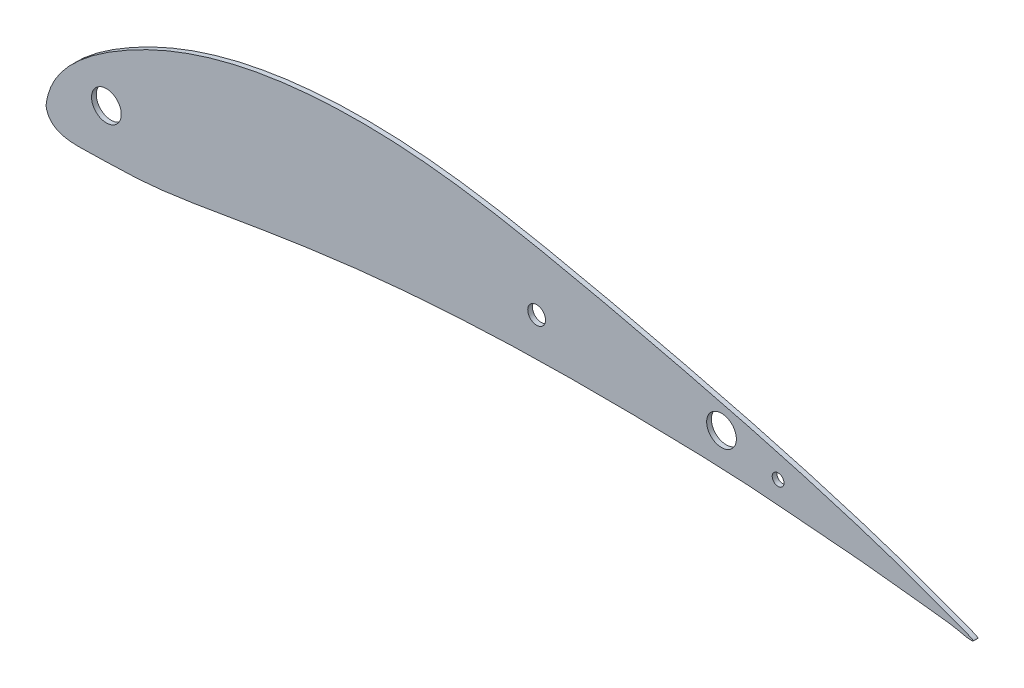
SolidWorks part; units mm, degrees
material "Balsa"
ref_plane "Front Plane" through (0, 0, 0) normal (0, 0, 1) x (1, 0, 0)
ref_plane "Top Plane" through (0, 0, 0) normal (0, 1, 0) x (1, 0, 0)
ref_plane "Right Plane" through (0, 0, 0) normal (1, 0, 0) x (0, 0, -1)
sketch "Sketch1" plane through (0, 0, 0) normal (0, 0, 1) x (1, 0, 0)
  spline S0 degree 3 poles (0.0006, 0.0001) (0.8106, 7.3592) (8.6491, 17.8566) (26.2867, 29.9752) (52.1111, 42.0692) (89.5976, 49.2908) (131.4008, 47.8848) (173.2567, 40.0411) (217.9611, 29.613) (256.9521, 19.5289) (290.3598, 8.711) (301.2732, 4.3828) (314.8169, -0.5162) (309.8463, 0.0001) knots 0 0 0 0 0.060864 0.113688 0.188609 0.312909 0.448482 0.557612 0.691544 0.852438 0.929756 0.976058 1 1 1 1
  spline S1 degree 3 poles (309.8463, 0.0001) (303.9568, 1.471) (293.9895, 2.094) (276.264, 4.5144) (260.8463, 5.4274) (235.8588, 7.8703) (205.1014, 8.8381) (157.7186, 9.0307) (110.4973, 6.1815) (66.5062, -0.5867) (36.4547, -6.0985) (15.3166, -6.1891) (1.2307, -6.9241) (0.0006, 0.0001) knots 0 0 0 0 0.057787 0.095275 0.171021 0.205339 0.335319 0.464904 0.658702 0.785512 0.893517 0.943092 1 1 1 1
extrude "Boss-Extrude1" add sketch "Sketch1" along normal blind 1.5875
sketch "Sketch2" plane through (0, 0, 1.5875) normal (0, 0, 1) x (1, 0, 0)
  line L0 (227.2963, 19.0501) -> (20.32, 10.16) construction
  line L1 (20.32, 10.16) -> (227.2963, 10.16) construction
  line L2 (227.2963, 10.16) -> (227.2963, 19.0501) construction
  circle A0 centre (20.32, 10.16) radius 5
  circle A1 centre (227.2963, 19.0501) radius 5
  circle A2 centre (246.3463, 14.2241) radius 1.9844
  dimension "D2" = 10
  dimension "D3" = 10
  dimension "D6" = 20.32
  dimension "D9" = 3.9688
  dimension "D1" = 82.55
  dimension "D4" = 19.05
  dimension "D5" = 10.16
  dimension "D7" = 63.5
  dimension "D8" = 14.224
extrude "Cut-Extrude1" cut sketch "Sketch2" against normal through all
sketch "Sketch3" plane through (0, 0, 0) normal (0, 0, -1) x (-1, 0, 0)
  line L0 (-309.8463, 0.0001) -> (-259.6129, 0.0001)
  circle A0 centre (-165.1006, 21.5901) radius 3
  dimension "D1" = 6
  dimension "D2" = 165.1
  dimension "D3" = 21.59
extrude "Cut-Extrude2" cut sketch "Sketch3" against normal blind 2.54 contours A0
